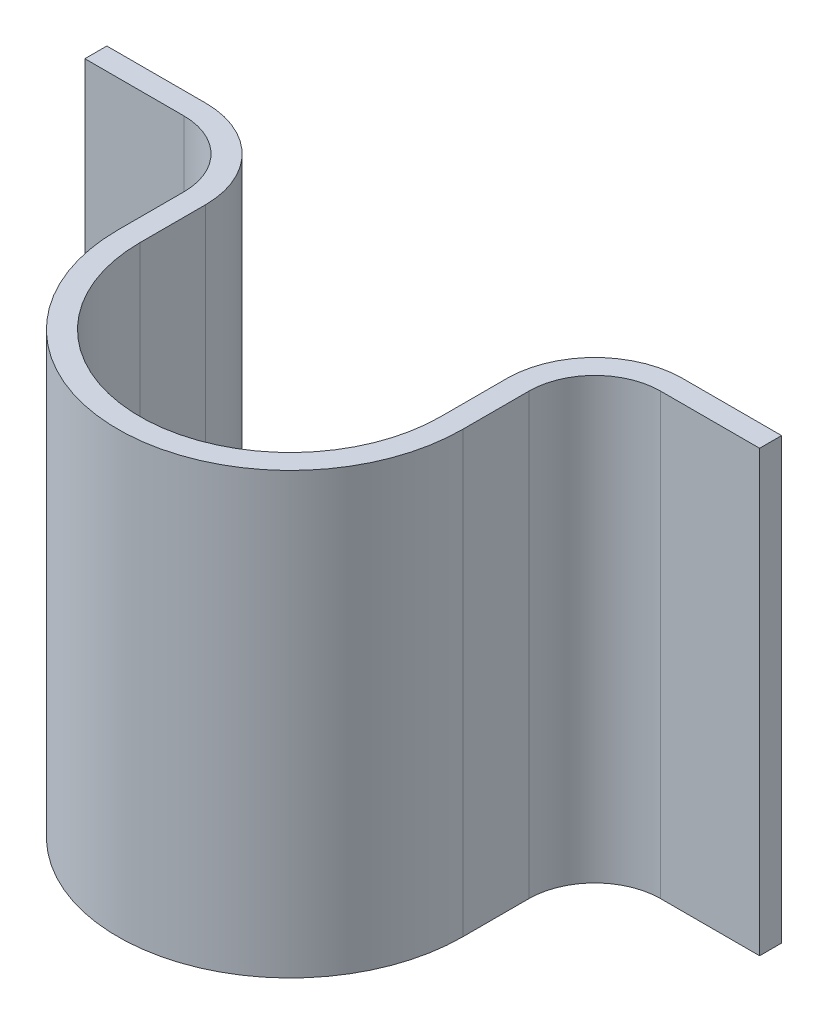
SolidWorks part; units mm, degrees
material "6061 Alloy"
ref_plane "Front Plane" through (0, 0, 0) normal (0, 0, 1) x (1, 0, 0)
ref_plane "Top Plane" through (0, 0, 0) normal (0, 1, 0) x (1, 0, 0)
ref_plane "Right Plane" through (0, 0, 0) normal (1, 0, 0) x (0, 0, -1)
sketch "Sketch1" plane through (0, 0, 0) normal (0, 1, 0) x (1, 0, 0)
  line L0 (13.7, 0) -> (13.7, 6)
  line L1 (21.7, 14) -> (30.7, 14)
  line L2 (0, 40.3997) -> (0, -48.6027) construction
  line L3 (-21.7, 14) -> (-30.7, 14)
  line L4 (-13.7, 0) -> (-13.7, 6)
  line L5 (21.7, 12) -> (30.7, 12)
  line L6 (15.7, 0) -> (15.7, 6)
  line L7 (-15.7, 0) -> (-15.7, 6)
  line L8 (-21.7, 12) -> (-30.7, 12)
  line L9 (30.7, 14) -> (30.7, 12)
  line L10 (-30.7, 14) -> (-30.7, 12)
  arc A0 (-13.7, 0) -> (13.7, 0) centre (0, 0) ccw
  arc A1 (13.7, 6) -> (21.7, 14) centre (21.7, 6) cw
  arc A2 (-13.7, 6) -> (-21.7, 14) centre (-21.7, 6) ccw
  arc A3 (15.7, 6) -> (21.7, 12) centre (21.7, 6) cw
  arc A4 (-15.7, 0) -> (15.7, 0) centre (0, 0) ccw
  arc A5 (-15.7, 6) -> (-21.7, 12) centre (-21.7, 6) ccw
  dimension "D1" = 8
  dimension "D2" = 13.7
  dimension "D4" = 9
  dimension "D5" = 6
  dimension "D3" = 2
extrude "Boss-Extrude1" add sketch "Sketch1" along normal mid plane 40
